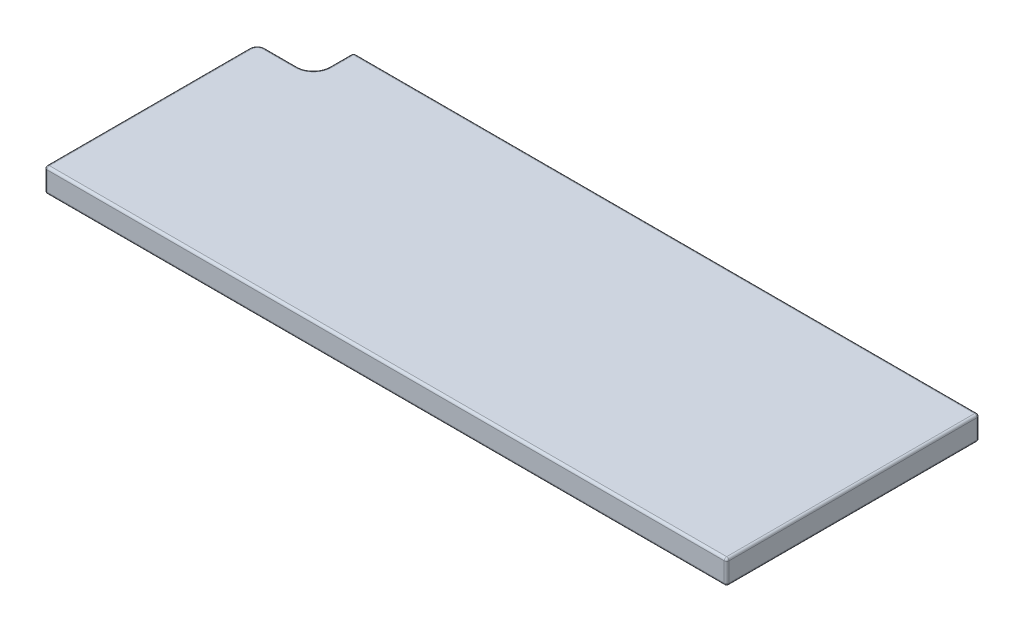
SolidWorks part; units mm, degrees
ref_plane "前视基准面" through (0, 0, 0) normal (0, 0, 1) x (1, 0, 0)
ref_plane "上视基准面" through (0, 0, 0) normal (0, 1, 0) x (1, 0, 0)
ref_plane "右视基准面" through (0, 0, 0) normal (1, 0, 0) x (0, 0, -1)
sketch "草图1" plane through (0, 0, 0) normal (0, 1, 0) x (1, 0, 0)
  line L2 (-425, 140) -> (-425, -115)
  line L3 (-425, -115) -> (425, -115)
  line L4 (425, 200) -> (425, -115)
  line L5 (-355, 200) -> (425, 200)
  line L13 (-415, 150) -> (-375, 150)
  line L14 (-355, 200) -> (-355, 170)
  arc A2 (-375, 150) -> (-355, 170) centre (-375, 170) ccw
  arc A3 (-425, 140) -> (-415, 150) centre (-415, 140) cw
  point P0 (0, 0)
  point P5 (0, 115)
  point P11 (-355, 150)
  point P14 (-425, 150)
  dimension "D2" = 50
  dimension "D3" = 70
  dimension "D4" = 20
  dimension "D5" = 10
  dimension "D1" = 850
  dimension "230" = 315
extrude "凸台-拉伸1" add sketch "草图1" along normal blind 30
fillet "圆角2" radius 3 20 edges at (-355, 15, -200) (425, 15, -200) (-425, 15, 115) (425, 15, 115) (35, 0, -200) (-355, 0, -185) (-360.8579, 0, -155.8579) (-395, 0, -150) (-422.0711, 0, -147.0711) (-425, 0, -12.5) (0, 0, 115) (425, 0, -42.5) (0, 30, 115) (-425, 30, -12.5) (-422.0711, 30, -147.0711) (-395, 30, -150) (-360.8579, 30, -155.8579) (-355, 30, -185) (35, 30, -200) (425, 30, -42.5)
